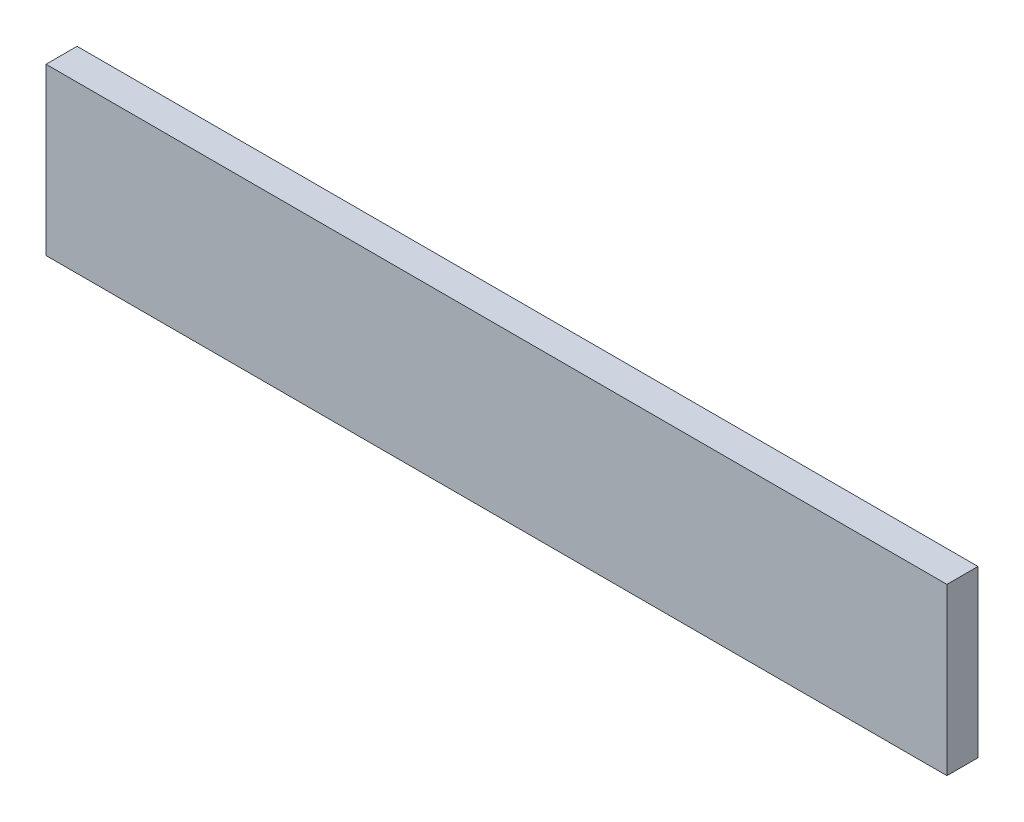
SolidWorks part; units mm, degrees
ref_plane "Front Plane" through (0, 0, 0) normal (0, 0, 1) x (1, 0, 0)
ref_plane "Top Plane" through (0, 0, 0) normal (0, 1, 0) x (1, 0, 0)
ref_plane "Right Plane" through (0, 0, 0) normal (1, 0, 0) x (0, 0, -1)
sketch "Sketch1" plane through (0, 0, 0) normal (0, 1, 0) x (1, 0, 0)
  line L1 (0, 0) -> (43.5, 0)
  line L2 (0, 0) -> (0, 1.5)
  line L3 (0, 1.5) -> (43.5, 1.5)
  line L4 (43.5, 0) -> (43.5, 1.5)
  dimension "D1" = 43.5
  dimension "D2" = 1.5
extrude "Boss-Extrude1" add sketch "Sketch1" along normal blind 8
